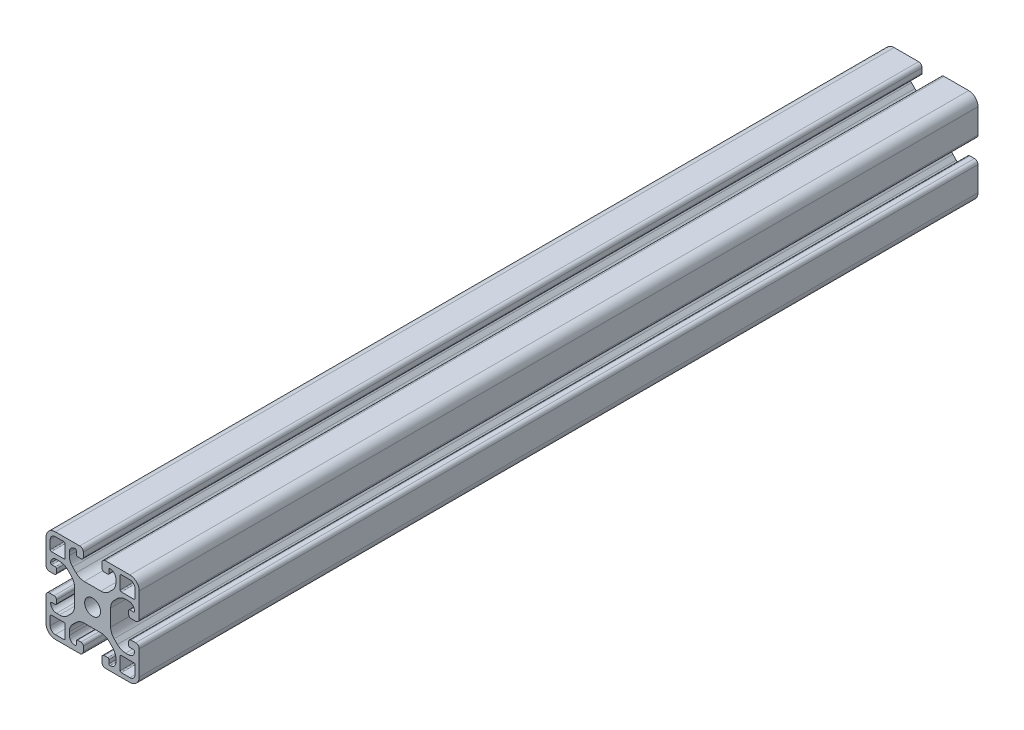
SolidWorks part; units mm, degrees
ref_plane "Plan de face" through (0, 0, 0) normal (0, 0, 1) x (1, 0, 0)
ref_plane "Plan de dessus" through (0, 0, 0) normal (0, 1, 0) x (1, 0, 0)
ref_plane "Plan de droite" through (0, 0, 0) normal (1, 0, 0) x (0, 0, -1)
ref_plane "Plan1" through (0, 0, -30) normal (0, 0, -1) x (-1, 0, 0)
sketch "Esquisse1" plane through (0, 0, -30) normal (0, 0, -1) x (-1, 0, 0)
  line L0 (-4.5, 15) -> (-4.5, 13.5)
  line L1 (-4, 13) -> (-2.5, 13)
  line L2 (-4.5, 10) -> (-5.8076, 10)
  line L3 (-9.3431, 11.4645) -> (-10.7855, 12.9069)
  line L4 (-12.25, 16.4424) -> (-12.25, 23.5576)
  line L5 (-10.7855, 27.0931) -> (-9.3431, 28.5355)
  line L6 (-5.8076, 30) -> (-4.5, 30)
  line L7 (-2.5, 27) -> (-4, 27)
  line L8 (-4.5, 26.5) -> (-4.5, 25)
  line L9 (-3.5, 24) -> (-1.5, 24)
  line L10 (0, 25.5) -> (0, 36)
  line L11 (-4, 40) -> (-14.5, 40)
  line L12 (-16, 38.5) -> (-16, 36.5)
  line L13 (-15, 35.5) -> (-13.5, 35.5)
  line L14 (-13, 36) -> (-13, 37.5)
  line L15 (-10, 35.5) -> (-10, 34.1924)
  line L16 (-11.4645, 30.6569) -> (-12.9069, 29.2145)
  line L17 (-16.4424, 27.75) -> (-23.5576, 27.75)
  line L18 (-27.0931, 29.2145) -> (-28.5355, 30.6569)
  line L19 (-30, 34.1924) -> (-30, 35.5)
  line L20 (-27, 37.5) -> (-27, 36)
  line L21 (-26.5, 35.5) -> (-25, 35.5)
  line L22 (-24, 36.5) -> (-24, 38.5)
  line L23 (-25.5, 40) -> (-36, 40)
  line L24 (-40, 36) -> (-40, 25.5)
  line L25 (-38.5, 24) -> (-36.5, 24)
  line L26 (-35.5, 25) -> (-35.5, 26.5)
  line L27 (-36, 27) -> (-37.5, 27)
  line L28 (-35.5, 30) -> (-34.1924, 30)
  line L29 (-30.6569, 28.5355) -> (-29.2145, 27.0931)
  line L30 (-27.75, 23.5576) -> (-27.75, 16.4424)
  line L31 (-29.2145, 12.9069) -> (-30.6569, 11.4645)
  line L32 (-34.1924, 10) -> (-35.5, 10)
  line L33 (-37.5, 13) -> (-36, 13)
  line L34 (-35.5, 13.5) -> (-35.5, 15)
  line L35 (-36.5, 16) -> (-38.5, 16)
  line L36 (-40, 14.5) -> (-40, 4)
  line L37 (-36, 0) -> (-25.5, 0)
  line L38 (-24, 1.5) -> (-24, 3.5)
  line L39 (-25, 4.5) -> (-26.5, 4.5)
  line L40 (-27, 4) -> (-27, 2.5)
  line L41 (-30, 4.5) -> (-30, 5.8076)
  line L42 (-28.5355, 9.3431) -> (-27.0931, 10.7855)
  line L43 (-23.5576, 12.25) -> (-16.4424, 12.25)
  line L44 (-12.9069, 10.7855) -> (-11.4645, 9.3431)
  line L45 (-10, 5.8076) -> (-10, 4.5)
  line L46 (-13, 2.5) -> (-13, 4)
  line L47 (-13.5, 4.5) -> (-15, 4.5)
  line L48 (-16, 3.5) -> (-16, 1.5)
  line L49 (-14.5, 0) -> (-4, 0)
  line L50 (0, 4) -> (0, 14.5)
  line L51 (-1.5, 16) -> (-3.5, 16)
  line L52 (-4, 1.8) -> (-7.7, 1.8)
  line L53 (-8.2, 2.3) -> (-8.2, 7.7)
  line L54 (-7.7, 8.2) -> (-2.3, 8.2)
  line L55 (-1.8, 7.7) -> (-1.8, 4)
  line L56 (-38.2, 4) -> (-38.2, 7.7)
  line L57 (-37.7, 8.2) -> (-32.3, 8.2)
  line L58 (-31.8, 7.7) -> (-31.8, 2.3)
  line L59 (-32.3, 1.8) -> (-36, 1.8)
  line L60 (-36, 38.2) -> (-32.3, 38.2)
  line L61 (-31.8, 37.7) -> (-31.8, 32.3)
  line L62 (-32.3, 31.8) -> (-37.7, 31.8)
  line L63 (-38.2, 32.3) -> (-38.2, 36)
  line L64 (-1.8, 36) -> (-1.8, 32.3)
  line L65 (-2.3, 31.8) -> (-7.7, 31.8)
  line L66 (-8.2, 32.3) -> (-8.2, 37.7)
  line L67 (-7.7, 38.2) -> (-4, 38.2)
  arc A0 (-4.5, 13.5) -> (-4, 13) centre (-4, 13.5) ccw
  arc A1 (-2.5, 13) -> (-2, 12.5) centre (-2.5, 12.5) cw
  arc A2 (-2, 12.5) -> (-4.5, 10) centre (-4.5, 12.5) cw
  arc A3 (-5.8076, 10) -> (-9.3431, 11.4645) centre (-5.8076, 15) cw
  arc A4 (-10.7855, 12.9069) -> (-12.25, 16.4424) centre (-7.25, 16.4424) cw
  arc A5 (-12.25, 23.5576) -> (-10.7855, 27.0931) centre (-7.25, 23.5576) cw
  arc A6 (-9.3431, 28.5355) -> (-5.8076, 30) centre (-5.8076, 25) cw
  arc A7 (-4.5, 30) -> (-2, 27.5) centre (-4.5, 27.5) cw
  arc A8 (-2, 27.5) -> (-2.5, 27) centre (-2.5, 27.5) cw
  arc A9 (-4, 27) -> (-4.5, 26.5) centre (-4, 26.5) ccw
  arc A10 (-4.5, 25) -> (-3.5, 24) centre (-3.5, 25) ccw
  arc A11 (-1.5, 24) -> (0, 25.5) centre (-1.5, 25.5) ccw
  arc A12 (0, 36) -> (-4, 40) centre (-4, 36) ccw
  arc A13 (-14.5, 40) -> (-16, 38.5) centre (-14.5, 38.5) ccw
  arc A14 (-16, 36.5) -> (-15, 35.5) centre (-15, 36.5) ccw
  arc A15 (-13.5, 35.5) -> (-13, 36) centre (-13.5, 36) ccw
  arc A16 (-13, 37.5) -> (-12.5, 38) centre (-12.5, 37.5) cw
  arc A17 (-12.5, 38) -> (-10, 35.5) centre (-12.5, 35.5) cw
  arc A18 (-10, 34.1924) -> (-11.4645, 30.6569) centre (-15, 34.1924) cw
  arc A19 (-12.9069, 29.2145) -> (-16.4424, 27.75) centre (-16.4424, 32.75) cw
  arc A20 (-23.5576, 27.75) -> (-27.0931, 29.2145) centre (-23.5576, 32.75) cw
  arc A21 (-28.5355, 30.6569) -> (-30, 34.1924) centre (-25, 34.1924) cw
  arc A22 (-30, 35.5) -> (-27.5, 38) centre (-27.5, 35.5) cw
  arc A23 (-27.5, 38) -> (-27, 37.5) centre (-27.5, 37.5) cw
  arc A24 (-27, 36) -> (-26.5, 35.5) centre (-26.5, 36) ccw
  arc A25 (-25, 35.5) -> (-24, 36.5) centre (-25, 36.5) ccw
  arc A26 (-24, 38.5) -> (-25.5, 40) centre (-25.5, 38.5) ccw
  arc A27 (-36, 40) -> (-40, 36) centre (-36, 36) ccw
  arc A28 (-40, 25.5) -> (-38.5, 24) centre (-38.5, 25.5) ccw
  arc A29 (-36.5, 24) -> (-35.5, 25) centre (-36.5, 25) ccw
  arc A30 (-35.5, 26.5) -> (-36, 27) centre (-36, 26.5) ccw
  arc A31 (-37.5, 27) -> (-38, 27.5) centre (-37.5, 27.5) cw
  arc A32 (-38, 27.5) -> (-35.5, 30) centre (-35.5, 27.5) cw
  arc A33 (-34.1924, 30) -> (-30.6569, 28.5355) centre (-34.1924, 25) cw
  arc A34 (-29.2145, 27.0931) -> (-27.75, 23.5576) centre (-32.75, 23.5576) cw
  arc A35 (-27.75, 16.4424) -> (-29.2145, 12.9069) centre (-32.75, 16.4424) cw
  arc A36 (-30.6569, 11.4645) -> (-34.1924, 10) centre (-34.1924, 15) cw
  arc A37 (-35.5, 10) -> (-38, 12.5) centre (-35.5, 12.5) cw
  arc A38 (-38, 12.5) -> (-37.5, 13) centre (-37.5, 12.5) cw
  arc A39 (-36, 13) -> (-35.5, 13.5) centre (-36, 13.5) ccw
  arc A40 (-35.5, 15) -> (-36.5, 16) centre (-36.5, 15) ccw
  arc A41 (-38.5, 16) -> (-40, 14.5) centre (-38.5, 14.5) ccw
  arc A42 (-40, 4) -> (-36, 0) centre (-36, 4) ccw
  arc A43 (-25.5, 0) -> (-24, 1.5) centre (-25.5, 1.5) ccw
  arc A44 (-24, 3.5) -> (-25, 4.5) centre (-25, 3.5) ccw
  arc A45 (-26.5, 4.5) -> (-27, 4) centre (-26.5, 4) ccw
  arc A46 (-27, 2.5) -> (-27.5, 2) centre (-27.5, 2.5) cw
  arc A47 (-27.5, 2) -> (-30, 4.5) centre (-27.5, 4.5) cw
  arc A48 (-30, 5.8076) -> (-28.5355, 9.3431) centre (-25, 5.8076) cw
  arc A49 (-27.0931, 10.7855) -> (-23.5576, 12.25) centre (-23.5576, 7.25) cw
  arc A50 (-16.4424, 12.25) -> (-12.9069, 10.7855) centre (-16.4424, 7.25) cw
  arc A51 (-11.4645, 9.3431) -> (-10, 5.8076) centre (-15, 5.8076) cw
  arc A52 (-10, 4.5) -> (-12.5, 2) centre (-12.5, 4.5) cw
  arc A53 (-12.5, 2) -> (-13, 2.5) centre (-12.5, 2.5) cw
  arc A54 (-13, 4) -> (-13.5, 4.5) centre (-13.5, 4) ccw
  arc A55 (-15, 4.5) -> (-16, 3.5) centre (-15, 3.5) ccw
  arc A56 (-16, 1.5) -> (-14.5, 0) centre (-14.5, 1.5) ccw
  arc A57 (-4, 0) -> (0, 4) centre (-4, 4) ccw
  arc A58 (0, 14.5) -> (-1.5, 16) centre (-1.5, 14.5) ccw
  arc A59 (-3.5, 16) -> (-4.5, 15) centre (-3.5, 15) ccw
  circle A60 centre (-20, 20) radius 3.4
  arc A61 (-1.8, 4) -> (-4, 1.8) centre (-4, 4) cw
  arc A62 (-7.7, 1.8) -> (-8.2, 2.3) centre (-7.7, 2.3) cw
  arc A63 (-8.2, 7.7) -> (-7.7, 8.2) centre (-7.7, 7.7) cw
  arc A64 (-2.3, 8.2) -> (-1.8, 7.7) centre (-2.3, 7.7) cw
  arc A65 (-36, 1.8) -> (-38.2, 4) centre (-36, 4) cw
  arc A66 (-38.2, 7.7) -> (-37.7, 8.2) centre (-37.7, 7.7) cw
  arc A67 (-32.3, 8.2) -> (-31.8, 7.7) centre (-32.3, 7.7) cw
  arc A68 (-31.8, 2.3) -> (-32.3, 1.8) centre (-32.3, 2.3) cw
  arc A69 (-38.2, 36) -> (-36, 38.2) centre (-36, 36) cw
  arc A70 (-32.3, 38.2) -> (-31.8, 37.7) centre (-32.3, 37.7) cw
  arc A71 (-31.8, 32.3) -> (-32.3, 31.8) centre (-32.3, 32.3) cw
  arc A72 (-37.7, 31.8) -> (-38.2, 32.3) centre (-37.7, 32.3) cw
  arc A73 (-4, 38.2) -> (-1.8, 36) centre (-4, 36) cw
  arc A74 (-1.8, 32.3) -> (-2.3, 31.8) centre (-2.3, 32.3) cw
  arc A75 (-7.7, 31.8) -> (-8.2, 32.3) centre (-7.7, 32.3) cw
  arc A76 (-8.2, 37.7) -> (-7.7, 38.2) centre (-7.7, 37.7) cw
extrude "Boss.-Extru.1" add sketch "Esquisse1" against normal blind 360
